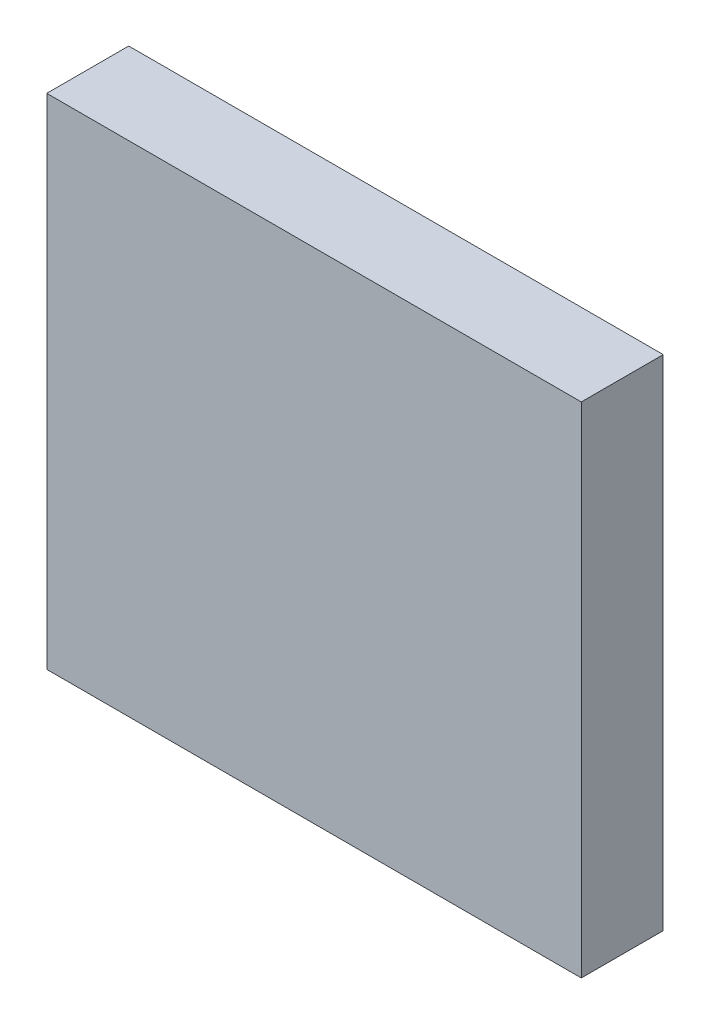
SolidWorks part; units mm, degrees
ref_plane "Front Plane" through (0, 0, 0) normal (0, 0, 1) x (1, 0, 0)
ref_plane "Top Plane" through (0, 0, 0) normal (0, 1, 0) x (1, 0, 0)
ref_plane "Right Plane" through (0, 0, 0) normal (1, 0, 0) x (0, 0, -1)
sketch "Sketch1" plane through (0, 0, 0) normal (0, 0, 1) x (1, 0, 0)
  line L1 (-9.525, -8.89) -> (9.525, -8.89)
  line L2 (-9.525, -8.89) -> (-9.525, 8.89)
  line L3 (-9.525, 8.89) -> (9.525, 8.89)
  line L4 (9.525, -8.89) -> (9.525, 8.89)
  line L5 (-9.525, -8.89) -> (9.525, 8.89) construction
  line L6 (-9.525, 8.89) -> (9.525, -8.89) construction
  point P0 (0, 0)
  dimension "D1" = 17.78
  dimension "D2" = 19.05
extrude "Boss-Extrude1" add sketch "Sketch1" along normal blind 2.921
